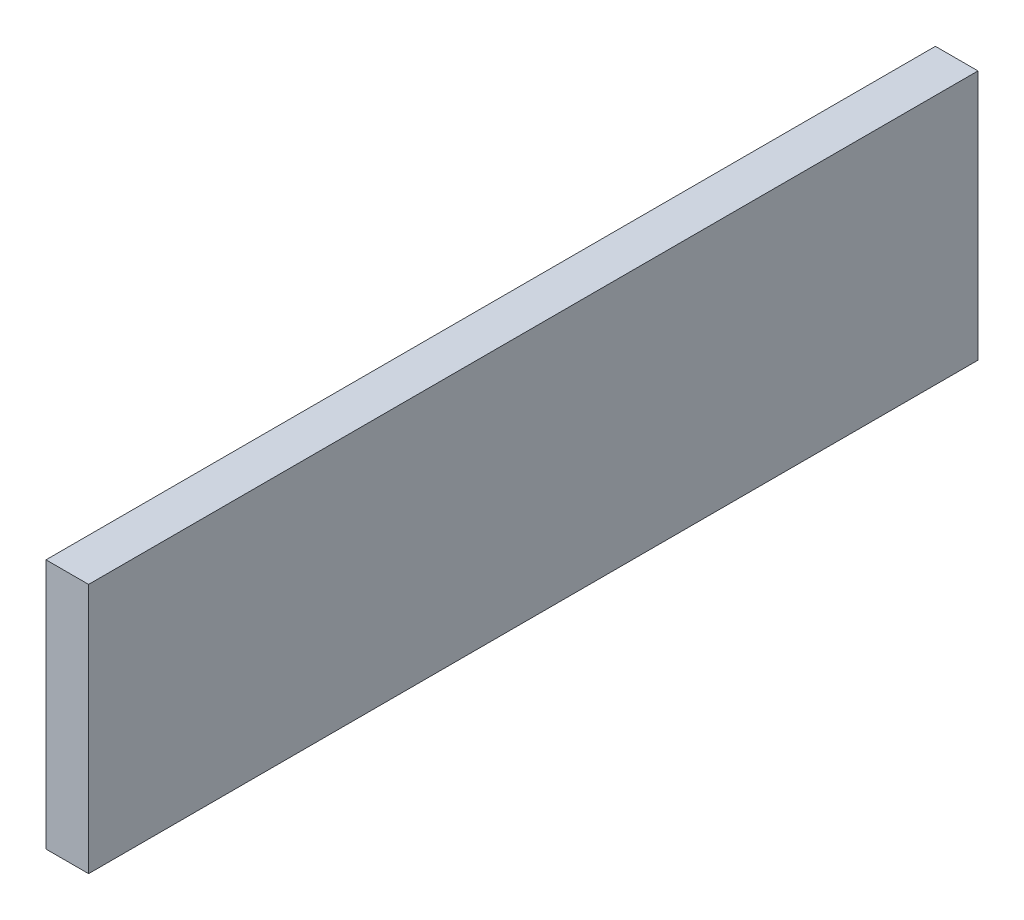
SolidWorks part; units mm, degrees
ref_plane "Front Plane" through (0, 0, 0) normal (0, 0, 1) x (1, 0, 0)
ref_plane "Top Plane" through (0, 0, 0) normal (0, 1, 0) x (1, 0, 0)
ref_plane "Right Plane" through (0, 0, 0) normal (1, 0, 0) x (0, 0, -1)
sketch "Sketch1" plane through (0, 0, 0) normal (0, 1, 0) x (1, 0, 0)
  line L1 (0, 0) -> (1.7, 0)
  line L2 (0, 0) -> (0, -35.5)
  line L3 (0, -35.5) -> (1.7, -35.5)
  line L4 (1.7, 0) -> (1.7, -35.5)
  dimension "D1" = 35.5
  dimension "D2" = 1.7
extrude "Boss-Extrude1" add sketch "Sketch1" along normal blind 10
